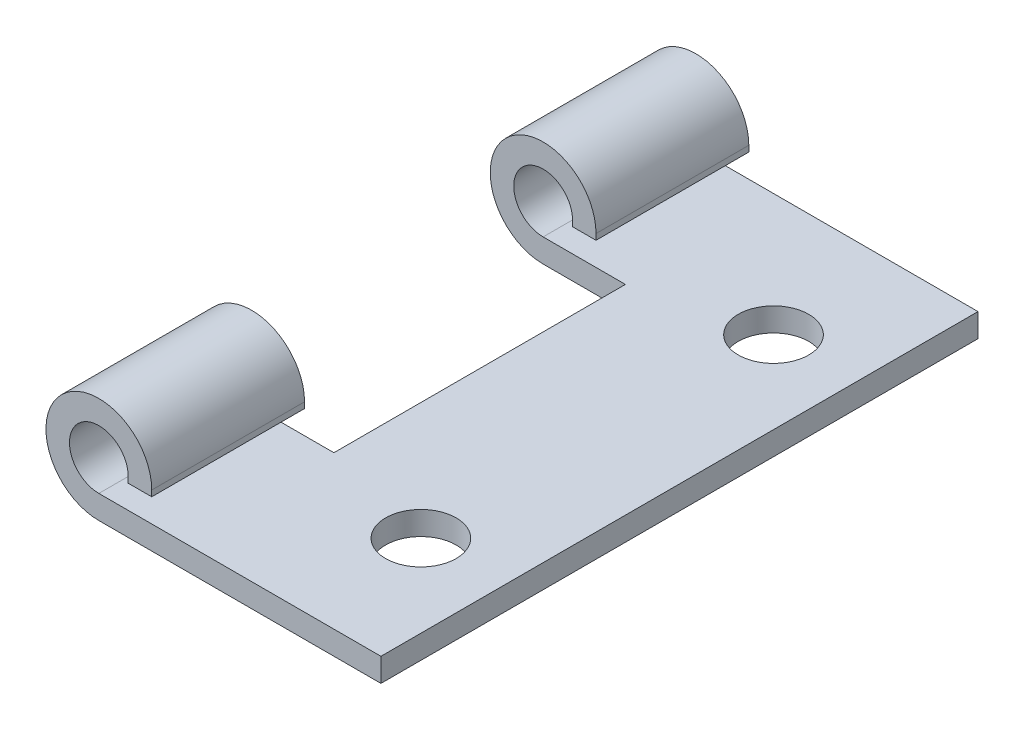
SolidWorks part; units mm, degrees
ref_plane "Alzado" through (0, 0, 0) normal (0, 0, 1) x (1, 0, 0)
ref_plane "Planta" through (0, 0, 0) normal (0, 1, 0) x (1, 0, 0)
ref_plane "Vista lateral" through (0, 0, 0) normal (1, 0, 0) x (0, 0, -1)
sketch "Croquis1" plane through (0, 0, 0) normal (0, 0, 1) x (1, 0, 0)
  line L8 (0, -2.25) -> (12, -2.25)
  line L9 (12, -2.25) -> (12, -1.25)
  line L10 (12, -1.25) -> (1.8708, -1.25)
  line L11 (1.25, -0.25) -> (2.2361, -0.25)
  line L12 (1.25, 0) -> (1.25, -0.25)
  line L13 (2.25, 0) -> (2.25, -0.25)
  line L14 (2.25, -0.25) -> (2.2361, -0.25)
  line L15 (1.8708, -1.25) -> (0, -1.25)
  arc A2 (1.25, 0) -> (0, -1.25) centre (0, 0) ccw
  arc A3 (2.25, 0) -> (0, -2.25) centre (0, 0) ccw
  dimension "D2" = 2.5
  dimension "D3" = 1
  dimension "D1" = 12
  dimension "D4" = 1
  dimension "D5" = 1
extrude "Saliente-Extruir1" add sketch "Croquis1" along normal blind 25.4
sketch "Croquis4" plane through (0, -2.25, 0) normal (0, -1, 0) x (1, 0, 0)
  line L0 (-2.25, 25.4) -> (-2.25, 0) construction
  line L1 (-2.25, 18.9) -> (3.5, 18.9)
  line L2 (-2.25, 18.9) -> (-2.25, 6.5)
  line L3 (-2.25, 6.5) -> (3.5, 6.5)
  line L4 (3.5, 18.9) -> (3.5, 6.5)
  line L5 (8.5, 5.2) -> (8.5, 20.2) construction
  line L6 (12, 12.7) -> (3.5, 12.7) construction
  line L7 (12, 25.4) -> (12, 0) construction
  line L8 (0, 25.4) -> (12, 25.4) construction
  circle A0 centre (8.5, 20.2) radius 1.5
  circle A1 centre (8.5, 5.2) radius 1.5
  point P14 (8.5, 12.7)
  dimension "D3" = 3
  dimension "D1" = 8.5
  dimension "D2" = 6.5
  dimension "D4" = 15
  dimension "D5" = 3.5
extrude "Cortar-Extruir3" cut sketch "Croquis4" against normal through all
